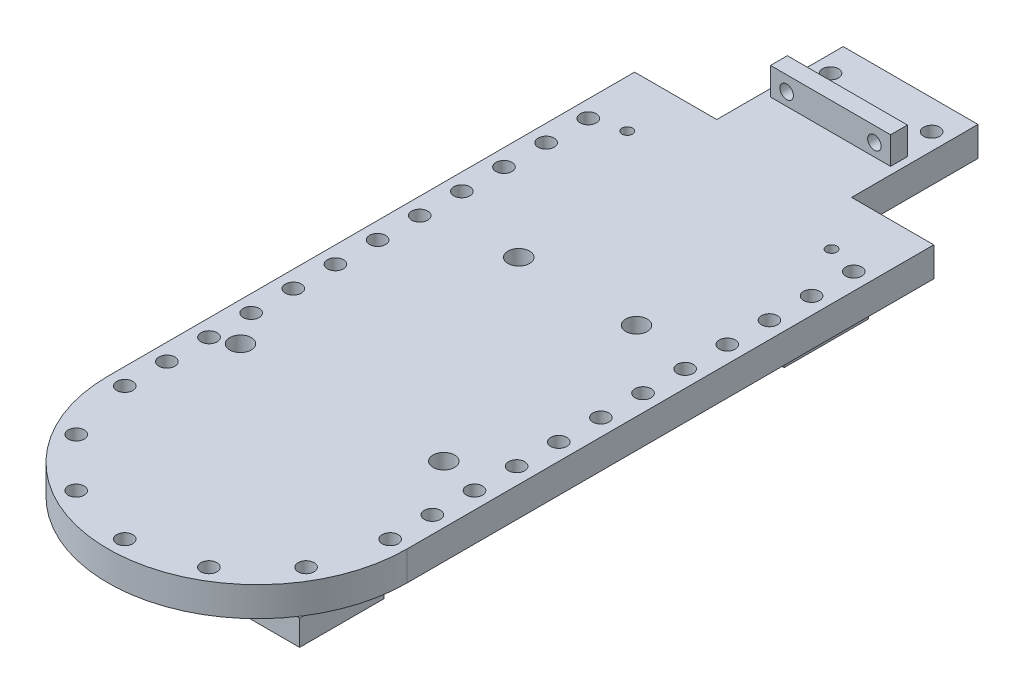
SolidWorks part; units mm, degrees
ref_plane "Front Plane" through (0, 0, 0) normal (0, 0, 1) x (1, 0, 0)
ref_plane "Top Plane" through (0, 0, 0) normal (0, 1, 0) x (1, 0, 0)
ref_plane "Right Plane" through (0, 0, 0) normal (1, 0, 0) x (0, 0, -1)
sketch "Sketch2" plane through (0, 0, 0) normal (0, 1, 0) x (1, 0, 0)
  line L1 (0, 0) -> (71, 0)
  line L2 (0, 0) -> (0, -120)
  line L4 (71, 0) -> (71, -120)
  arc A0 (0, -120) -> (71, -120) centre (35.5, -120) ccw
  dimension "D1" = 120
  dimension "D2" = 71
extrude "Main body" add sketch "Sketch2" along normal blind 7
sketch "Sketch3" plane through (0, 7, 0) normal (0, 1, 0) x (1, 0, 0)
  line L0 (35.5, 0) -> (35.5, 70.5768) construction
  line L1 (71, 0) -> (0, 0) construction
  line L3 (19.5, 0) -> (51.5, 0)
  line L4 (19.5, 0) -> (19.5, 20)
  line L5 (19.5, 20) -> (51.5, 20)
  line L6 (51.5, 0) -> (51.5, 20)
  dimension "D1" = 20
  dimension "D2" = 32
extrude "Boss-Extrude2" add sketch "Sketch3" against normal up to surface (7 mm away) up to face at (35.5, 0, 68.875)
sketch "Sketch4" plane through (0, 7, 0) normal (0, 1, 0) x (1, 0, 0)
  line L0 (35.5, 20) -> (35.5, 8.5949) construction
  line L1 (21.25, 20) -> (49.75, 20)
  line L2 (21.25, 20) -> (21.25, 16)
  line L3 (21.25, 16) -> (49.75, 16)
  line L4 (49.75, 20) -> (49.75, 16)
  line L5 (51.5, 20) -> (19.5, 20) construction
  dimension "D1" = 4
  dimension "D2" = 28.5
extrude "Boss-Extrude3" add sketch "Sketch4" along normal blind 6.5
sketch "Sketch7" plane through (0, 0, -20) normal (0, 0, -1) x (-1, 0, 0)
  line L0 (-51.5, 0) -> (-51.5, 7) construction
  line L1 (-19.5, 0) -> (-51.5, 0)
  line L2 (-19.5, 0) -> (-19.5, 7)
  line L3 (-19.5, 7) -> (-51.5, 7)
  line L4 (-51.5, 0) -> (-51.5, 7)
  line L5 (-71, 7) -> (-51.5, 7) construction
extrude "Boss-Extrude4" add sketch "Sketch7" along normal blind 15
sketch "Sketch10" plane through (0, 7, 0) normal (0, 1, 0) x (1, 0, 0)
  line L0 (4, -120) -> (4, -110) construction
  line L1 (35.5, -120) -> (4, -120) construction
  line L2 (4, 0) -> (4, -120)
  line L3 (4, 0) -> (4, -120) construction
  line L5 (67, -120) -> (4, -120) construction
  line L6 (35.5, -153.4) -> (35.5, -120) construction
  line L7 (67, 0) -> (67, -120) construction
  line L8 (67, -120) -> (67, -110) construction
  circle A0 centre (4, -120) radius 1.9
  circle A1 centre (4, -110) radius 1.9
  arc A2 (4, -120) -> (67, -120) centre (35.5, -120) ccw
  arc A3 (4, -120) -> (67, -120) centre (35.5, -120) ccw construction
  circle A4 centre (4, -100) radius 1.9
  circle A5 centre (4, -90) radius 1.9
  circle A6 centre (4, -80) radius 1.9
  circle A7 centre (4, -70) radius 1.9
  circle A8 centre (4, -60) radius 1.9
  circle A9 centre (4, -50) radius 1.9
  circle A10 centre (4, -40) radius 1.9
  circle A11 centre (4, -30) radius 1.9
  circle A12 centre (4, -20) radius 1.9
  circle A13 centre (4, -10) radius 1.9
  circle A14 centre (8.2202, -135.75) radius 1.9
  circle A15 centre (19.75, -147.2798) radius 1.9
  circle A16 centre (35.5, -151.5) radius 1.9
  circle A17 centre (51.25, -147.2798) radius 1.9
  circle A18 centre (62.7798, -135.75) radius 1.9
  circle A19 centre (67, -120) radius 1.9
  circle A20 centre (67, -10) radius 1.9
  circle A21 centre (67, -20) radius 1.9
  circle A22 centre (67, -30) radius 1.9
  circle A23 centre (67, -40) radius 1.9
  circle A24 centre (67, -50) radius 1.9
  circle A25 centre (67, -60) radius 1.9
  circle A26 centre (67, -70) radius 1.9
  circle A27 centre (67, -80) radius 1.9
  circle A28 centre (67, -90) radius 1.9
  circle A29 centre (67, -100) radius 1.9
  circle A30 centre (67, -110) radius 1.9
  dimension "D3" = 3.8
  dimension "D4" = 10
  dimension "D1" = 4
  dimension "D2" = 4
  dimension "D5" = 12
  dimension "D6" = 7
extrude "Cut-Extrude5" cut sketch "Sketch10" against normal up to surface (7 mm away) up to face at (37.9375, 0, 25.6875)
sketch "Sketch13" plane through (0, 0, 0) normal (0, -1, 0) x (1, 0, 0)
  line L0 (35.5, -35) -> (35.5, 155.5) construction
  line L1 (51.5, -35) -> (19.5, -35) construction
  line L2 (30.5, 120) -> (40.5, 120) construction
  line L3 (30.5, 130) -> (40.5, 130)
  line L4 (30.5, 130) -> (30.5, 110)
  line L5 (30.5, 110) -> (40.5, 110)
  line L6 (40.5, 130) -> (40.5, 110)
  line L7 (30.5, 15) -> (40.5, 15)
  line L8 (30.5, 15) -> (30.5, -5)
  line L9 (30.5, -5) -> (40.5, -5)
  line L10 (40.5, 15) -> (40.5, -5)
  line L11 (40.5, 5) -> (30.5, 5) construction
  line L12 (71, 0) -> (51.5, 0) construction
  arc A0 (71, 120) -> (0, 120) centre (35.5, 120) ccw construction
  dimension "D1" = 10
  dimension "D2" = 20
  dimension "D3" = 115
  dimension "D4" = 5
extrude "Boss-Extrude5" add sketch "Sketch13" along normal blind 10
sketch "Sketch14" plane through (0, -10, 0) normal (0, -1, 0) x (1, 0, 0)
  line L0 (35.5, -5) -> (35.5, 130) construction
  line L1 (30.5, -5) -> (40.5, -5) construction
  line L2 (40.5, 130) -> (30.5, 130) construction
  line L3 (35.5, 62.5) -> (71, 62.5) construction
  line L4 (71, 120) -> (71, 0) construction
  line L6 (15.5, 130) -> (55.5, 130)
  line L7 (15.5, 130) -> (15.5, 110)
  line L8 (15.5, 110) -> (55.5, 110)
  line L9 (55.5, 130) -> (55.5, 110)
  line L10 (30.5, 110) -> (40.5, 110) construction
  line L11 (40.5, 130) -> (30.5, 130) construction
  line L12 (30.5, 120) -> (15.5, 120) construction
  line L13 (30.5, 130) -> (30.5, 110) construction
  line L14 (23, 120) -> (23, 130) construction
  line L15 (15.5, -5) -> (55.5, -5)
  line L16 (55.5, -5) -> (55.5, 15)
  line L17 (15.5, -5) -> (15.5, 15)
  line L18 (15.5, 15) -> (55.5, 15)
  circle A0 centre (23, 125) radius 1.9
  circle A1 centre (23, 115) radius 1.9
  circle A2 centre (48, 125) radius 1.9
  circle A3 centre (48, 115) radius 1.9
  circle A4 centre (48, 0) radius 1.9
  circle A5 centre (48, 10) radius 1.9
  circle A6 centre (23, 0) radius 1.9
  circle A7 centre (23, 10) radius 1.9
  dimension "D2" = 3.8
  dimension "D1" = 40
extrude "Boss-Extrude6" add sketch "Sketch14" along normal blind 6
sketch "Sketch15" plane through (0, 0, 0) normal (0, -1, 0) x (1, 0, 0)
  circle A0 centre (24.3162, 46.805) radius 1.5621 construction
  circle A1 centre (24.3162, 46.805) radius 2.5621
  circle A2 centre (52.2562, 46.805) radius 2.5621
  circle A3 centre (24.3162, 46.805) radius 1.5621 construction
  circle A4 centre (52.2562, 46.805) radius 1.5621 construction
  circle A5 centre (52.2562, 46.805) radius 1.5621 construction
  circle A6 centre (57.3362, 97.605) radius 1.5621 construction
  circle A7 centre (57.3362, 97.605) radius 1.5621 construction
  circle A8 centre (9.0762, 97.605) radius 1.5621 construction
  circle A9 centre (9.0762, 97.605) radius 1.5621 construction
  circle A10 centre (57.3362, 97.605) radius 2.5621
  circle A11 centre (9.0762, 97.605) radius 2.5621
  dimension "D1" = 1
sketch "Sketch17" plane through (0, 7, 0) normal (0, 1, 0) x (1, 0, 0)
  line L2 (40.5, 5) -> (55.5, 5) construction
  line L4 (0, 0) -> (71, 0)
  line L5 (0, 0) -> (0, 5)
  line L6 (0, 5) -> (71, 5)
  line L7 (71, 0) -> (71, 5)
extrude "Boss-Extrude7" add sketch "Sketch17" against normal blind 7
sketch "Sketch19" plane through (0, 7, 0) normal (0, 1, 0) x (1, 0, 0)
  line L0 (11.25, -8) -> (59.75, -8) construction
  line L1 (35.5, -8) -> (35.5, -13.303) construction
  line L2 (19.5, 35) -> (19.5, 5) construction
  line L3 (51.5, 5) -> (51.5, 35) construction
  line L4 (19.5, 5) -> (0, 5) construction
  circle A0 centre (11.25, -8) radius 1.25
  circle A2 centre (59.75, -8) radius 1.25
  dimension "D1" = 2.5
  dimension "D2" = 48.5
  dimension "D3" = 13
extrude "Cut-Extrude7" cut sketch "Sketch19" against normal blind 7
sketch "Sketch21" plane through (0, 0, -20) normal (0, 0, -1) x (-1, 0, 0)
  line L0 (-45.915, 10) -> (-25.085, 10) construction
  line L1 (-35.5, 10) -> (-35.5, 24.8088) construction
  line L2 (-49.75, 13.5) -> (-49.75, 7) construction
  line L3 (-21.25, 13.5) -> (-21.25, 7) construction
  line L4 (-21.25, 7) -> (-49.75, 7) construction
  circle A0 centre (-45.915, 10) radius 1.6
  circle A1 centre (-25.085, 10) radius 1.6
  dimension "D1" = 3.2
  dimension "D2" = 20.83
  dimension "D3" = 3
extrude "Cut-Extrude9" cut sketch "Sketch21" against normal blind 4
sketch "Sketch22" plane through (0, 7, 0) normal (0, 1, 0) x (1, 0, 0)
  line L0 (23.5, 28) -> (47.5, 28) construction
  line L1 (35.5, 28) -> (35.5, 36.9857) construction
  line L2 (19.5, 35) -> (19.5, 5) construction
  line L3 (51.5, 5) -> (51.5, 35) construction
  line L4 (19.5, 35) -> (51.5, 35) construction
  circle A0 centre (23.5, 28) radius 1.9
  circle A1 centre (47.5, 28) radius 1.9
  dimension "D1" = 3.8
  dimension "D2" = 24
  dimension "D3" = 7
extrude "Cut-Extrude10" cut sketch "Sketch22" against normal blind 7
extrude "DUE mount" cut sketch "Sketch15" against normal through all
